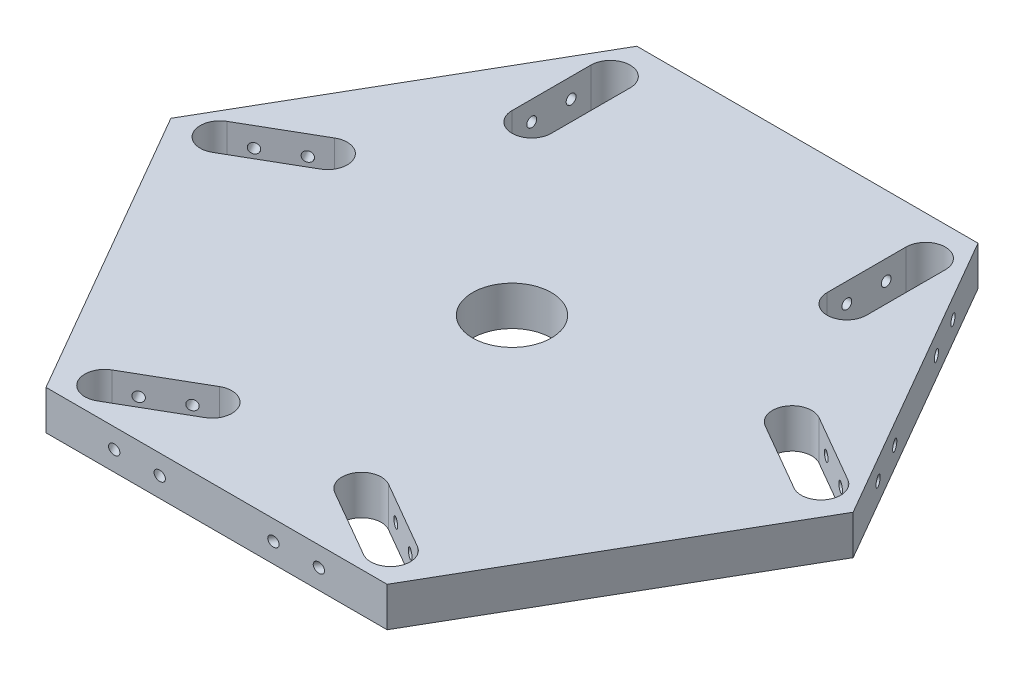
SolidWorks part; units mm, degrees
ref_plane "Front Plane" through (0, 0, 0) normal (0, 0, 1) x (1, 0, 0)
ref_plane "Top Plane" through (0, 0, 0) normal (0, 1, 0) x (1, 0, 0)
ref_plane "Right Plane" through (0, 0, 0) normal (1, 0, 0) x (0, 0, -1)
sketch "Sketch1" plane through (0, 0, 0) normal (0, 1, 0) x (1, 0, 0)
  line L7 (-43.3013, -75) -> (43.3013, -75)
  line L8 (43.3013, -75) -> (86.6025, 0)
  line L9 (86.6025, 0) -> (43.3013, 75)
  line L10 (43.3013, 75) -> (-43.3013, 75)
  line L11 (-43.3013, 75) -> (-86.6025, 0)
  line L12 (-86.6025, 0) -> (-43.3013, -75)
  circle A0 centre (0, 0) radius 75 construction
  dimension "D1" = 150
extrude "Boss-Extrude1" add sketch "Sketch1" along normal blind 10
sketch "Sketch3" plane through (0, 10, 0) normal (0, 1, 0) x (1, 0, 0)
  line L0 (-76.2917, 2.141) -> (-58.9711, 12.141) construction
  line L3 (-78.7917, 6.4711) -> (-61.4711, 16.4711)
  line L4 (-73.7917, -2.1891) -> (-56.4711, 7.8109)
  line L5 (-36.2917, -67.141) -> (-18.9711, -57.141) construction
  line L6 (-38.7917, -62.8109) -> (-21.4711, -52.8109)
  line L7 (-33.7917, -71.4711) -> (-16.4711, -61.4711)
  line L8 (-86.6025, 0) -> (-43.3013, -75) construction
  arc A2 (-78.7917, 6.4711) -> (-73.7917, -2.1891) centre (-76.2917, 2.141) ccw
  arc A3 (-56.4711, 7.8109) -> (-61.4711, 16.4711) centre (-58.9711, 12.141) ccw
  arc A4 (-38.7917, -62.8109) -> (-33.7917, -71.4711) centre (-36.2917, -67.141) ccw
  arc A5 (-16.4711, -61.4711) -> (-21.4711, -52.8109) centre (-18.9711, -57.141) ccw
  point P2 (-67.6314, 7.141)
  point P9 (-27.6314, -62.141)
  point P16 (-64.9519, -37.5)
  dimension "D7" = 5
  dimension "D8" = 5
  dimension "D1" = 20
  dimension "D2" = 20
  dimension "D3" = 40
  dimension "D4" = 40
  dimension "D5" = 10
  dimension "D6" = 10
extrude "Cut-Extrude1" cut sketch "Sketch3" against normal blind 20
sketch "Sketch4" plane through (17.5, 0, 30.3109) normal (0.5, 0, 0.866) x (0.866, 0, -0.5)
  line L0 (-65, 10) -> (-65, 0) construction
  line L1 (-65, 0) -> (-65, 10) construction
  line L2 (-45, 10) -> (-45, 0) construction
  line L3 (-65, 10) -> (-45, 10) construction
  circle A0 centre (-60, 5) radius 1.25
  circle A1 centre (-50, 5) radius 1.25
  point P14 (-55, 10)
  dimension "D1" = 2.5
  dimension "D2" = 10
  dimension "D3" = 5
  dimension "D4" = 5
extrude "Cut-Extrude2" cut sketch "Sketch4" against normal through all both and the other way through all
sketch "Sketch6" plane through (0, 10, 0) normal (0, 1, 0) x (1, 0, 0)
  circle A0 centre (0, 0) radius 10
  dimension "D1" = 20
extrude "Cut-Extrude3" cut sketch "Sketch6" against normal through all both
pattern_circular "CirPattern1" count 3 over 360 about axis through (0, 0, 0) along (0, 1, 0) of "Cut-Extrude1", "Cut-Extrude2"
